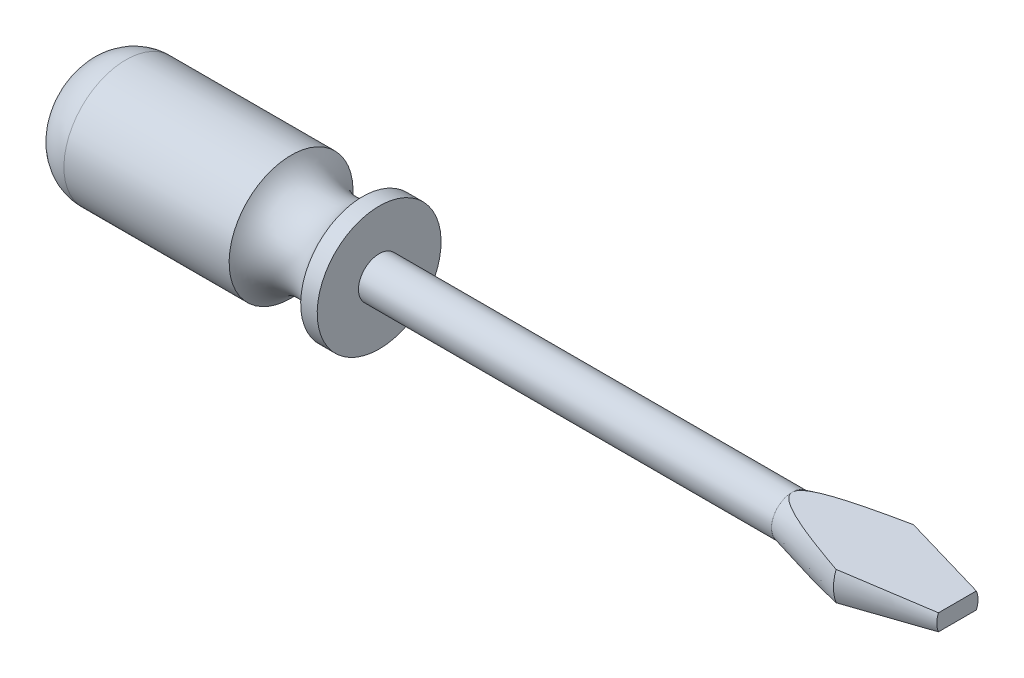
SolidWorks part; units mm, degrees
ref_plane "Front Plane" through (0, 0, 0) normal (0, 0, 1) x (1, 0, 0)
ref_plane "Top Plane" through (0, 0, 0) normal (0, 1, 0) x (1, 0, 0)
ref_plane "Right Plane" through (0, 0, 0) normal (1, 0, 0) x (0, 0, -1)
sketch "Sketch1" plane through (0, 0, 0) normal (0, 0, 1) x (1, 0, 0)
  line L1 (6.9279, 8.89) -> (57.7279, 8.89)
  line L6 (84.8049, 8.89) -> (79.7249, 8.89)
  line L15 (262.6049, -3.81) -> (262.6049, -10.16)
  line L16 (-5.2064, -10.16) -> (262.6049, -10.16) construction
  line L17 (84.8049, 8.89) -> (84.8049, -3.81)
  line L20 (262.6049, -10.16) -> (-5.2064, -10.16)
  line L22 (84.8049, -3.81) -> (211.8049, -3.81)
  line L23 (211.8049, -3.81) -> (237.2049, 2.54)
  line L24 (237.2049, 2.54) -> (262.6049, -3.81)
  arc A0 (79.7249, 8.89) -> (57.7279, 8.89) centre (68.7264, 15.24) cw
  arc A1 (-5.2064, -10.16) -> (6.9279, 8.89) centre (6.9279, -4.4995) cw
  dimension "D7" = 12.7
  dimension "D9" = 13.3895
  dimension "D1" = 25.4
  dimension "D2" = 6.35
  dimension "D3" = 50.8
  dimension "D4" = 5.08
  dimension "D5" = 12.7
revolve "Revolve6" add sketch "Sketch1" angle 360 about L16
sketch "Sketch2" plane through (0, 0, 0) normal (0, 0, 1) x (1, 0, 0)
sketch "Sketch3" plane through (0, 0, 0) normal (0, 0, 1) x (1, 0, 0)
  line L5 (211.8049, -3.81) -> (262.6049, -7.62)
  line L6 (237.2049, 2.54) -> (211.8049, -3.81) construction
  line L7 (211.8049, -3.81) -> (211.8049, 19.983)
  line L8 (211.8049, 19.983) -> (262.6049, 19.983)
  line L9 (262.6049, 19.983) -> (262.6049, -7.62)
  line L10 (262.6049, -40.303) -> (262.6049, -12.7)
  line L11 (211.8049, -16.51) -> (262.6049, -12.7)
  line L12 (211.8049, -16.51) -> (211.8049, -40.303)
  line L13 (211.8049, -40.303) -> (262.6049, -40.303)
extrude "Cut-Extrude2" cut sketch "Sketch3" against normal mid plane 50.8
